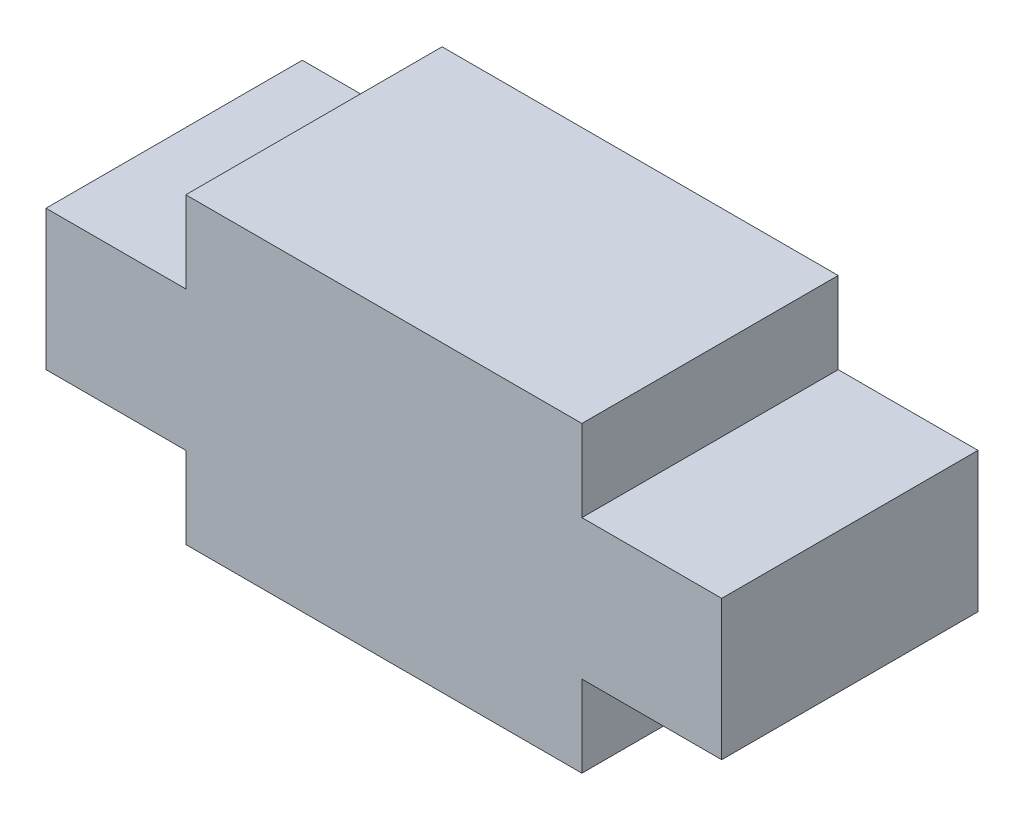
SolidWorks part; units mm, degrees
ref_plane "前视基准面" through (0, 0, 0) normal (0, 0, 1) x (1, 0, 0)
ref_plane "上视基准面" through (0, 0, 0) normal (0, 1, 0) x (1, 0, 0)
ref_plane "右视基准面" through (0, 0, 0) normal (1, 0, 0) x (0, 0, -1)
sketch "草图1" plane through (0, 0, 0) normal (0, 0, 1) x (1, 0, 0)
  line L0 (-1.45, -0.3) -> (-0.85, -0.3)
  line L1 (-0.85, -0.3) -> (-0.85, -0.65)
  line L2 (-0.85, -0.65) -> (0.85, -0.65)
  line L3 (0.85, -0.65) -> (0.85, -0.3)
  line L4 (0.85, -0.3) -> (1.45, -0.3)
  line L5 (1.45, -0.3) -> (1.45, 0.3)
  line L6 (1.45, 0.3) -> (0.85, 0.3)
  line L7 (0.85, 0.3) -> (0.85, 0.65)
  line L8 (0.85, 0.65) -> (-0.85, 0.65)
  line L9 (-0.85, 0.65) -> (-0.85, 0.3)
  line L10 (-0.85, 0.3) -> (-1.45, 0.3)
  line L11 (-1.45, 0.3) -> (-1.45, -0.3)
extrude "Component_Outline" add sketch "草图1" along normal blind 1.1 separate body
sketch3d "3D草图1"
  line L0 (0, 0, 0) -> (1, 0, 0)
  line L1 (0, 0, 0) -> (0, 1, 0)
  line L2 (0, 0, 0) -> (0, 0, 1)
  point P0 (0, 0, 0)
